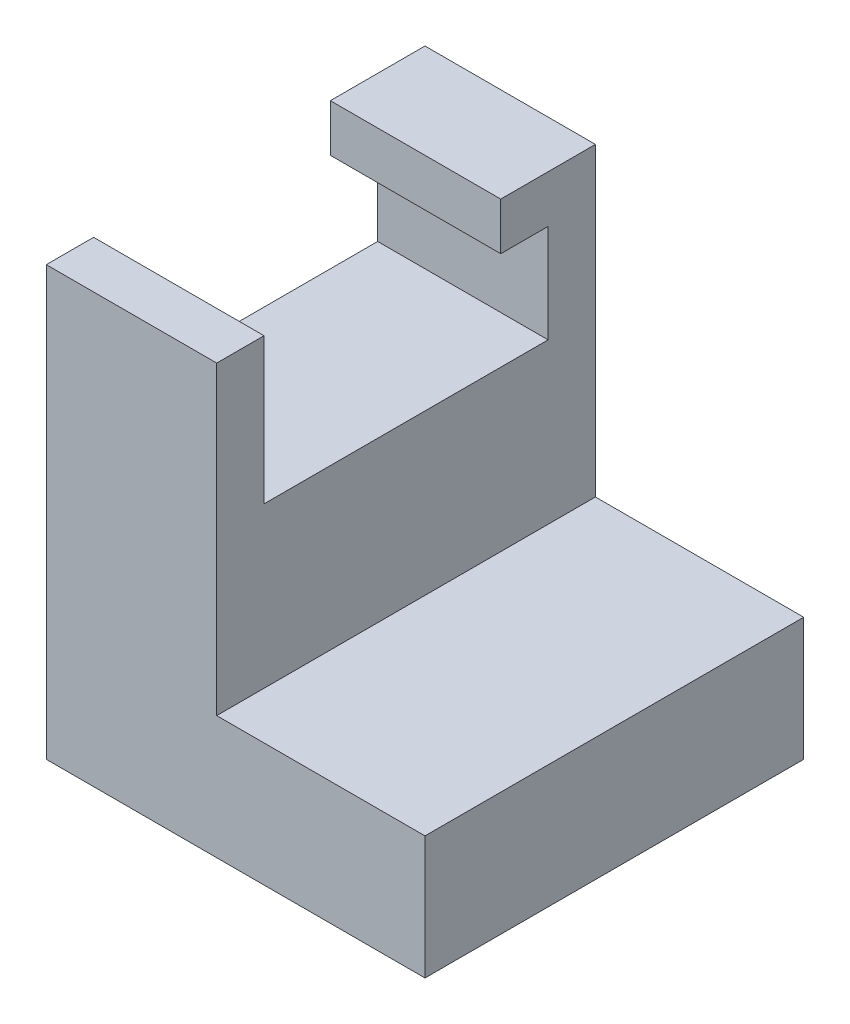
SolidWorks part; units mm, degrees
ref_plane "Front Plane" through (0, 0, 0) normal (0, 0, 1) x (1, 0, 0)
ref_plane "Top Plane" through (0, 0, 0) normal (0, 1, 0) x (1, 0, 0)
ref_plane "Right Plane" through (0, 0, 0) normal (1, 0, 0) x (0, 0, -1)
sketch "Sketch1" plane through (0, 0, 0) normal (0, 0, 1) x (1, 0, 0)
  line L0 (-17.2544, 42.0681) -> (-35.2544, 42.0681)
  line L1 (-35.2544, 42.0681) -> (-35.2544, -3.1819)
  line L2 (-35.2544, -3.1819) -> (4.7456, -3.1819)
  line L3 (4.7456, -3.1819) -> (4.7456, 9.8181)
  line L4 (4.7456, 9.8181) -> (-17.2544, 9.8181)
  line L5 (-17.2544, 42.0681) -> (-17.2544, 9.8181)
  dimension "D1" = 18
  dimension "D2" = 22
  dimension "D3" = 40
  dimension "D4" = 13
extrude "Boss-Extrude1" add sketch "Sketch1" along normal blind 40
sketch "Sketch2" plane through (-17.2544, 0, 0) normal (1, 0, 0) x (0, 0, -1)
  line L0 (-40, 42.0681) -> (0, 42.0681) construction
  line L1 (-35, 42.0681) -> (-10, 42.0681)
  line L2 (-35, 42.0681) -> (-35, 37.0681)
  line L3 (-35, 37.0681) -> (-10, 37.0681)
  line L4 (-10, 42.0681) -> (-10, 37.0681)
  line L5 (-40, 9.8181) -> (-40, 42.0681) construction
  point P8 (-10, 39.5681)
  dimension "D1" = 5
  dimension "D2" = 5
  dimension "D3" = 25
extrude "Cut-Extrude1" cut sketch "Sketch2" against normal blind 40
sketch "Sketch3" plane through (-17.2544, 0, 0) normal (1, 0, 0) x (0, 0, -1)
  line L0 (-35, 37.0681) -> (-10, 37.0681) construction
  line L1 (-5, 37.0681) -> (-35, 37.0681)
  line L2 (-5, 37.0681) -> (-5, 26.6891)
  line L3 (-5, 26.6891) -> (-35, 26.6891)
  line L4 (-35, 37.0681) -> (-35, 26.6891)
  line L5 (-40, 9.8181) -> (-40, 42.0681) construction
  dimension "D1" = 30
  dimension "D2" = 0
  dimension "D3" = 5
extrude "Cut-Extrude2" cut sketch "Sketch3" against normal blind 40
